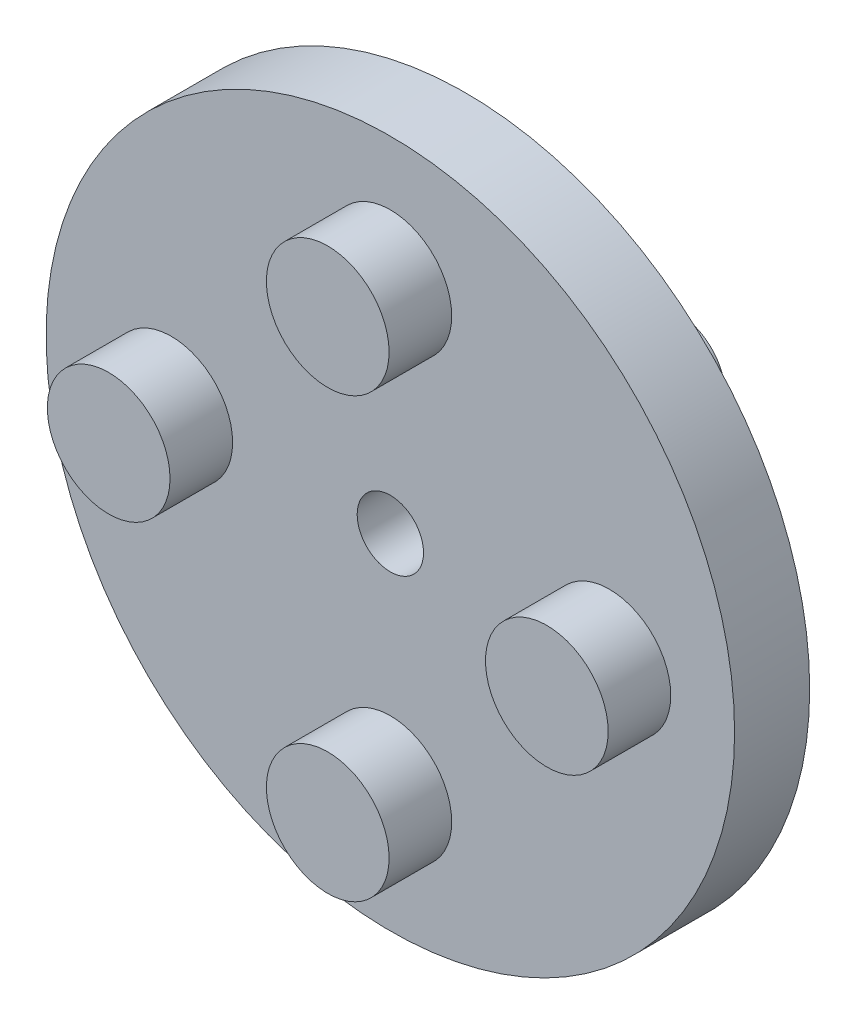
SolidWorks part; units mm, degrees
ref_plane "Front Plane" through (0, 0, 0) normal (0, 0, 1) x (1, 0, 0)
ref_plane "Top Plane" through (0, 0, 0) normal (0, 1, 0) x (1, 0, 0)
ref_plane "Right Plane" through (0, 0, 0) normal (1, 0, 0) x (0, 0, -1)
sketch "Sketch1" plane through (0, 0, 0) normal (0, 0, 1) x (1, 0, 0)
  circle A0 centre (0, 0) radius 27.5
  circle A1 centre (0, 0) radius 2.65
  dimension "D1" = 55
  dimension "D2" = 5.3
extrude "Boss-Extrude1" add sketch "Sketch1" along normal blind 6
sketch "Sketch2" plane through (0, 0, 6) normal (0, 0, 1) x (1, 0, 0)
  circle A6 centre (0, 0) radius 17.5 construction
  circle A7 centre (0, 17.5) radius 4.9
  circle A8 centre (17.5, 0) radius 4.9
  circle A9 centre (0, -17.5) radius 4.9
  circle A10 centre (-17.5, 0) radius 4.9
  point P13 (0, 0)
  dimension "D1" = 35
  dimension "D2" = 9.8
  dimension "D3" = 4
extrude "Boss-Extrude2" add sketch "Sketch2" along normal blind 5
sketch "Sketch3" plane through (0, 0, 0) normal (0, 0, -1) x (-1, 0, 0)
  circle A0 centre (0, 0) radius 2.65
  circle A1 centre (0, 0) radius 3.75
  dimension "D1" = 7.5
extrude "Boss-Extrude3" add sketch "Sketch3" along normal blind 17
